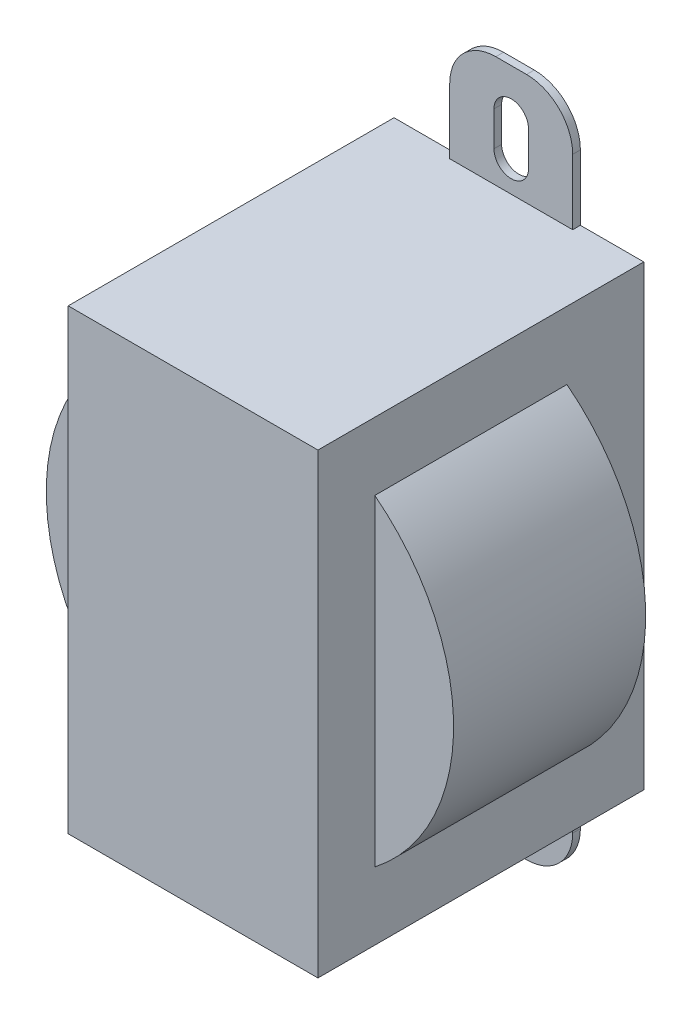
SolidWorks part; units mm, degrees
ref_plane "前视基准面" through (0, 0, 0) normal (0, 0, 1) x (1, 0, 0)
ref_plane "上视基准面" through (0, 0, 0) normal (0, 1, 0) x (1, 0, 0)
ref_plane "右视基准面" through (0, 0, 0) normal (1, 0, 0) x (0, 0, -1)
sketch "草图1" plane through (0, 0, 0) normal (0, 0, 1) x (1, 0, 0)
  line L0 (0, 107.8945) -> (0, -117.3589) construction
  line L1 (-16.25, 29.75) -> (16.25, 29.75)
  line L2 (-16.25, 29.75) -> (-16.25, -29.75)
  line L3 (-16.25, -29.75) -> (16.25, -29.75)
  line L4 (16.25, 29.75) -> (16.25, -29.75)
  line L5 (-105.0552, 0) -> (107.8945, 0) construction
  dimension "D1" = 32.5
  dimension "D2" = 59.5
extrude "拉伸1" add sketch "草图1" along normal blind 42.4
ref_plane "基准面1" through (0, 0, 10) normal (0, 0, 1) x (1, 0, 0)
sketch "草图2" plane through (0, 0, 10) normal (0, 0, 1) x (1, 0, 0)
  line L0 (-16.25, 20.9329) -> (16.25, 20.9329)
  line L1 (-16.25, 29.75) -> (-16.25, -29.75) construction
  line L2 (16.25, -29.75) -> (16.25, 29.75) construction
  line L3 (16.25, -20.9329) -> (-16.25, -20.9329)
  arc A0 (-16.25, 20.9329) -> (-16.25, -20.9329) centre (0, 0) ccw
  arc A1 (16.25, -20.9329) -> (16.25, 20.9329) centre (0, 0) ccw
  dimension "D1" = 26.5
extrude "拉伸2" add sketch "草图2" along normal blind 25
sketch "草图4" plane through (0, 0, 0) normal (0, 0, 1) x (1, 0, 0)
  line L0 (0, 48.5161) -> (0, -34.8903) construction
  line L1 (16.25, 29.75) -> (-16.25, 29.75) construction
  line L2 (-2, 44.25) -> (2, 44.25)
  line L3 (-8, 38.25) -> (-8, 29.75)
  line L4 (-8, 29.75) -> (8, 29.75)
  line L5 (8, 38.25) -> (8, 29.75)
  line L6 (-32.7557, 0) -> (34.5425, 0) construction
  line L7 (-2, -44.25) -> (2, -44.25)
  line L8 (-8, -38.25) -> (-8, -29.75)
  line L9 (-8, -29.75) -> (8, -29.75)
  line L10 (8, -38.25) -> (8, -29.75)
  line L11 (-2.25, 38.25) -> (-2.25, 33.75)
  line L12 (2.25, 38.25) -> (2.25, 33.75)
  line L13 (2.25, -38.25) -> (2.25, -33.75)
  line L14 (-2.25, -38.25) -> (-2.25, -33.75)
  arc A0 (-2.25, 33.75) -> (2.25, 33.75) centre (0, 33.75) ccw
  arc A1 (2.25, -38.25) -> (-2.25, -38.25) centre (0, -38.25) cw
  arc A2 (2.25, 38.25) -> (-2.25, 38.25) centre (0, 38.25) ccw
  arc A3 (-2.25, -33.75) -> (2.25, -33.75) centre (0, -33.75) cw
  arc A4 (8, 38.25) -> (2, 44.25) centre (2, 38.25) ccw
  arc A5 (-8, 38.25) -> (-2, 44.25) centre (-2, 38.25) cw
  arc A6 (8, -38.25) -> (2, -44.25) centre (2, -38.25) cw
  arc A7 (-8, -38.25) -> (-2, -44.25) centre (-2, -38.25) ccw
  point P29 (8, 44.25)
  point P32 (-8, 44.25)
  dimension "D4" = 4.5
  dimension "D5" = 4.5
  dimension "D6" = 6
  dimension "D7" = 6
  dimension "D1" = 14.5
  dimension "D2" = 16
  dimension "D3" = 67.5
extrude "拉伸3" add sketch "草图4" along normal blind 1
